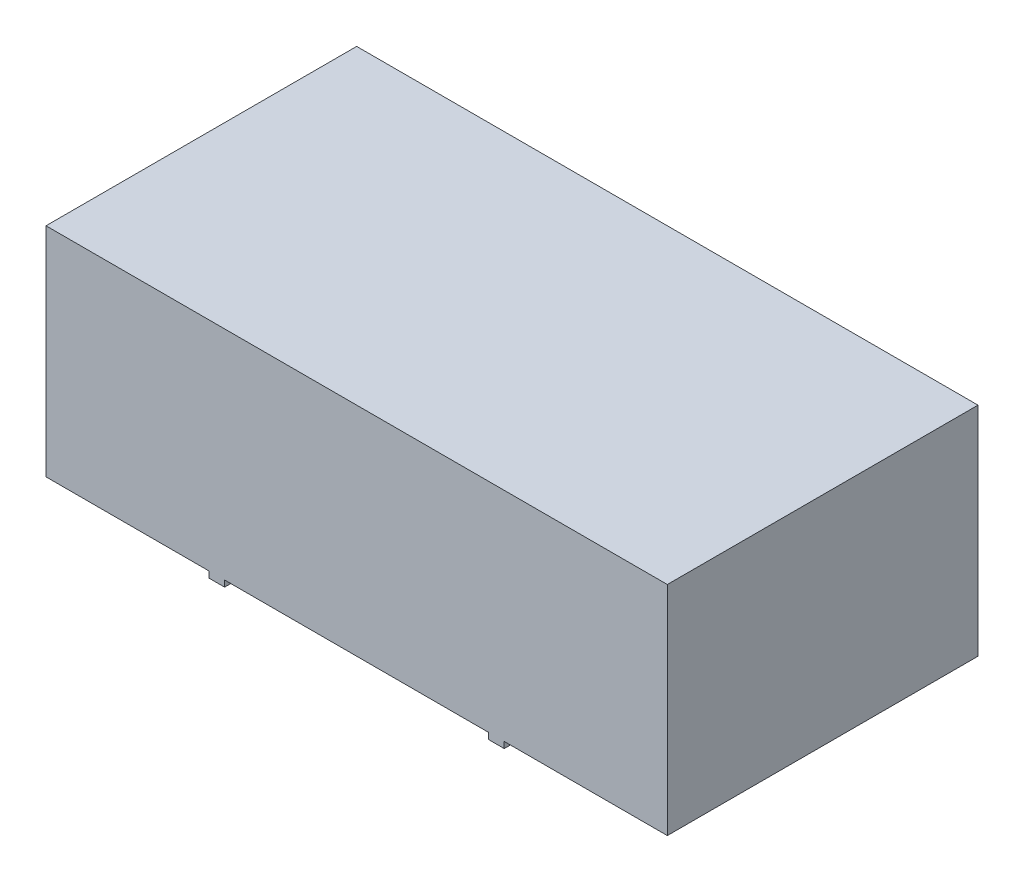
SolidWorks part; units mm, degrees
ref_plane "Front Plane" through (0, 0, 0) normal (0, 0, 1) x (1, 0, 0)
ref_plane "Top Plane" through (0, 0, 0) normal (0, 1, 0) x (1, 0, 0)
ref_plane "Right Plane" through (0, 0, 0) normal (1, 0, 0) x (0, 0, -1)
sketch "Sketch1" plane through (0, 0, 0) normal (0, 1, 0) x (1, 0, 0)
  line L1 (-100, 50) -> (100, 50)
  line L2 (-100, 50) -> (-100, -50)
  line L3 (-100, -50) -> (100, -50)
  line L4 (100, 50) -> (100, -50)
  line L5 (-100, 50) -> (100, -50) construction
  line L6 (-100, -50) -> (100, 50) construction
  point P0 (0, 0)
  dimension "D1" = 100
  dimension "D2" = 200
extrude "Boss-Extrude1" add sketch "Sketch1" along normal blind 70
sketch "Sketch2" plane through (0, 0, 0) normal (0, -1, 0) x (1, 0, 0)
  line L0 (100, -50) -> (-100, -50) construction
  line L1 (-42.5, 50) -> (42.5, 50)
  line L2 (-42.5, 50) -> (-42.5, -50)
  line L3 (-42.5, -50) -> (42.5, -50)
  line L4 (42.5, 50) -> (42.5, -50)
  line L5 (-42.5, 50) -> (42.5, -50) construction
  line L6 (-42.5, -50) -> (42.5, 50) construction
  line L8 (42.5, 50) -> (47.5, 50)
  line L9 (42.5, 50) -> (42.5, -50)
  line L10 (42.5, -50) -> (47.5, -50)
  line L11 (47.5, 50) -> (47.5, -50)
  line L12 (-42.5, 50) -> (-47.5, 50)
  line L13 (-42.5, 50) -> (-42.5, -50)
  line L14 (-42.5, -50) -> (-47.5, -50)
  line L15 (-47.5, 50) -> (-47.5, -50)
  point P0 (0, 0)
  line M7 (100, 50) -> (-100, 50)
  line M9 (-100, -50) -> (100, -50)
  dimension "D1" = 85
  dimension "D2" = 5
  dimension "D3" = 5
extrude "Boss-Extrude2" add sketch "Sketch2" along normal blind 2 contours L15 L2 M7 M9 | L11 L4 M7 M9
